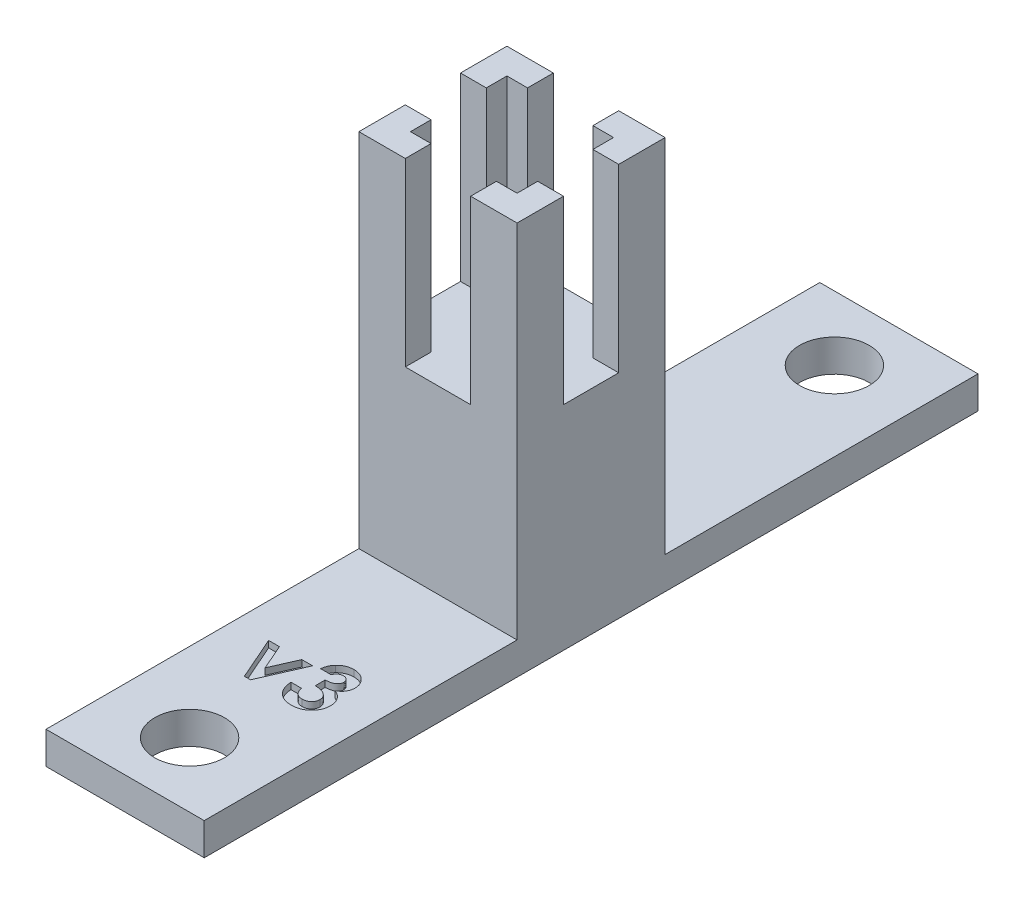
SolidWorks part; units mm, degrees
ref_plane "Front Plane" through (0, 0, 0) normal (0, 0, 1) x (1, 0, 0)
ref_plane "Top Plane" through (0, 0, 0) normal (0, 1, 0) x (1, 0, 0)
ref_plane "Right Plane" through (0, 0, 0) normal (1, 0, 0) x (0, 0, -1)
sketch "Sketch1" plane through (0, 0, 0) normal (0, 1, 0) x (1, 0, 0)
  line L0 (-5.25, 4.75) -> (-5.25, 2.718)
  line L1 (-5.25, -4.75) -> (5.25, -4.75) construction
  line L2 (-5.25, -4.75) -> (-5.25, 4.75) construction
  line L3 (-5.25, 4.75) -> (5.25, 4.75) construction
  line L4 (5.25, -4.75) -> (5.25, 4.75) construction
  line L5 (-5.25, -4.75) -> (5.25, 4.75) construction
  line L6 (-5.25, 4.75) -> (5.25, -4.75) construction
  line L7 (-5.25, 2.718) -> (-7.79, 2.718)
  line L8 (-7.79, 2.718) -> (-7.79, 7.29)
  line L9 (-7.79, 7.29) -> (-3.218, 7.29)
  line L10 (-3.218, 7.29) -> (-3.218, 4.75)
  line L11 (-3.218, 4.75) -> (-5.25, 4.75)
  line L12 (0, 4.75) -> (0, -4.75) construction
  line L13 (-5.25, 0) -> (5.25, 0) construction
  line L14 (7.79, 2.718) -> (7.79, 7.29)
  line L15 (5.25, 2.718) -> (7.79, 2.718)
  line L16 (5.25, 4.75) -> (5.25, 2.718)
  line L17 (3.218, 4.75) -> (5.25, 4.75)
  line L18 (3.218, 7.29) -> (3.218, 4.75)
  line L19 (7.79, 7.29) -> (3.218, 7.29)
  line L20 (5.25, -2.718) -> (7.79, -2.718)
  line L21 (5.25, -4.75) -> (5.25, -2.718)
  line L22 (3.218, -4.75) -> (5.25, -4.75)
  line L23 (3.218, -7.29) -> (3.218, -4.75)
  line L24 (7.79, -7.29) -> (3.218, -7.29)
  line L25 (7.79, -2.718) -> (7.79, -7.29)
  line L26 (-5.25, -2.718) -> (-7.79, -2.718)
  line L27 (-5.25, -4.75) -> (-5.25, -2.718)
  line L28 (-3.218, -4.75) -> (-5.25, -4.75)
  line L29 (-3.218, -7.29) -> (-3.218, -4.75)
  line L30 (-7.79, -7.29) -> (-3.218, -7.29)
  line L31 (-7.79, -2.718) -> (-7.79, -7.29)
  point P0 (0, 0)
  dimension "D1" = 10.5
  dimension "D2" = 9.5
  dimension "D3" = 2.54
  dimension "D4" = 2.032
extrude "Boss-Extrude1" add sketch "Sketch1" along normal blind 17.78
sketch "Sketch2" plane through (0, 0, 0) normal (0, -1, 0) x (-1, 0, 0)
  line L1 (7.79, -7.29) -> (-7.79, -7.29)
  line L2 (7.79, -7.29) -> (7.79, 7.29)
  line L3 (7.79, 7.29) -> (-7.79, 7.29)
  line L4 (-7.79, -7.29) -> (-7.79, 7.29)
extrude "Boss-Extrude2" add sketch "Sketch2" along normal blind 17.78
sketch "Sketch3" plane through (0, -17.78, 0) normal (0, -1, 0) x (-1, 0, 0)
  line L0 (0, 0) -> (7.79, 0) construction
  line L1 (-7.79, -38.1) -> (7.79, -38.1)
  line L2 (-7.79, -38.1) -> (-7.79, 38.1)
  line L3 (-7.79, 38.1) -> (7.79, 38.1)
  line L4 (7.79, -38.1) -> (7.79, 38.1)
  line L5 (-7.79, -38.1) -> (7.79, 38.1) construction
  line L6 (-7.79, 38.1) -> (7.79, -38.1) construction
  line L7 (7.79, -7.29) -> (7.79, 7.29) construction
  circle A0 centre (0, 31.75) radius 3.429
  circle A1 centre (0, -31.75) radius 3.429
  point P0 (0, 0)
  dimension "D2" = 6.858
  dimension "D3" = 31.75
  dimension "D4" = 76.2
extrude "Boss-Extrude3" add sketch "Sketch3" along normal blind 3.175
sketch "Sketch5" plane through (0, -17.78, 0) normal (0, 1, 0) x (1, 0, 0)
  line L0 (-7.79, -23.8163) -> (7.79, -23.8163) construction
  line L1 (-7.79, -38.1) -> (-7.79, -7.29) construction
  line L2 (7.79, -7.29) -> (7.79, -38.1) construction
  text T0 "<b>v3</b>" font "Century Gothic" height in points 22
extrude "Cut-Extrude3" cut sketch "Sketch5" against normal blind 0.635
